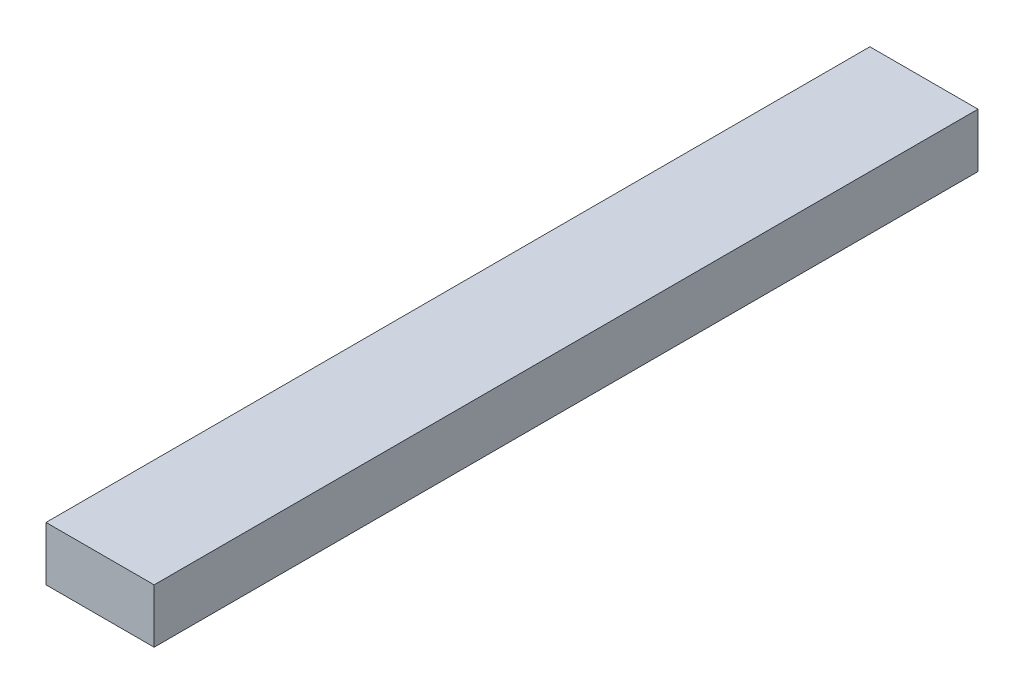
SolidWorks part; units mm, degrees
ref_plane "Front Plane" through (0, 0, 0) normal (0, 0, 1) x (1, 0, 0)
ref_plane "Top Plane" through (0, 0, 0) normal (0, 1, 0) x (1, 0, 0)
ref_plane "Right Plane" through (0, 0, 0) normal (1, 0, 0) x (0, 0, -1)
sketch "Sketch1" plane through (0, 0, 0) normal (0, 0, 1) x (1, 0, 0)
  line L1 (-30, -15) -> (30, -15)
  line L2 (-30, -15) -> (-30, 15)
  line L3 (-30, 15) -> (30, 15)
  line L4 (30, -15) -> (30, 15)
  line L5 (-30, -15) -> (30, 15) construction
  line L6 (-30, 15) -> (30, -15) construction
  point P0 (0, 0)
  dimension "D1" = 60
  dimension "D2" = 30
extrude "Boss-Extrude1" add sketch "Sketch1" along normal mid plane 457.2
